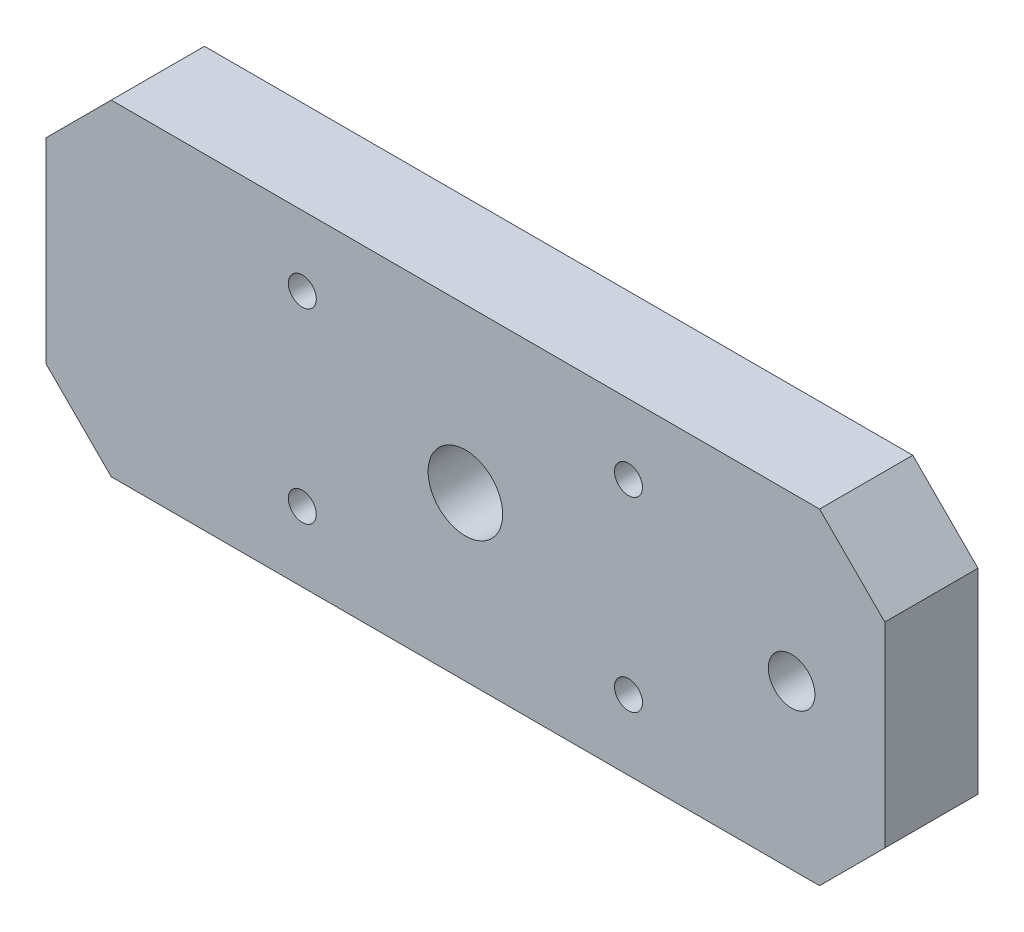
SolidWorks part; units mm, degrees
ref_plane "正面" through (0, 0, 0) normal (0, 0, 1) x (1, 0, 0)
ref_plane "平面" through (0, 0, 0) normal (0, 1, 0) x (1, 0, 0)
ref_plane "右側面" through (0, 0, 0) normal (1, 0, 0) x (0, 0, -1)
sketch "ｽｹｯﾁ1" plane through (0, 0, 0) normal (0, 0, 1) x (1, 0, 0)
  line L0 (0, 17.5) -> (0, -17.5) construction
  line L1 (-45, 17.5) -> (45, 17.5)
  line L2 (-45, 17.5) -> (-45, -17.5)
  line L3 (-45, -17.5) -> (45, -17.5)
  line L4 (45, 17.5) -> (45, -17.5)
  line L5 (45, 0) -> (35, 0) construction
  circle A0 centre (35, 0) radius 2.5
  circle A1 centre (0, 0) radius 4
  circle A2 centre (17.5, 10) radius 1.5
  circle A3 centre (17.5, -10) radius 1.5
  circle A4 centre (-17.5, 10) radius 1.5
  circle A5 centre (-17.5, -10) radius 1.5
  point P17 (0, 0)
  dimension "D3" = 5
  dimension "D4" = 10
  dimension "D5" = 3
  dimension "D6" = 35
  dimension "D7" = 20
  dimension "D8" = 8
  dimension "D1" = 90
  dimension "D2" = 35
extrude "ﾎﾞｽ - 押し出し1" add sketch "ｽｹｯﾁ1" along normal blind 10
chamfer "面取り1" distance 7 angle 45 4 edges at (-45, -17.5, 5) (45, -17.5, 5) (45, 17.5, 5) (-45, 17.5, 5)
